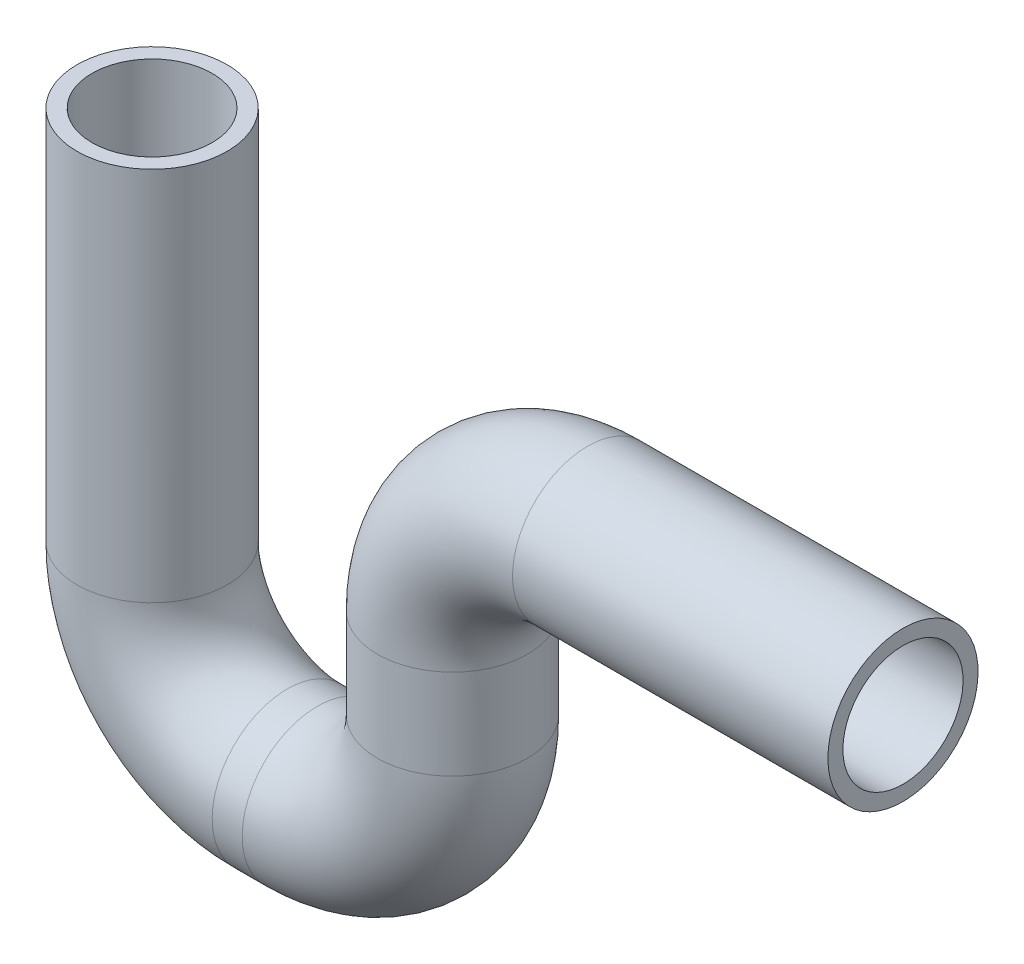
SolidWorks part; units mm, degrees
ref_plane "Alzado" through (0, 0, 0) normal (0, 0, 1) x (1, 0, 0)
ref_plane "Planta" through (0, 0, 0) normal (0, 1, 0) x (1, 0, 0)
ref_plane "Vista lateral" through (0, 0, 0) normal (1, 0, 0) x (0, 0, -1)
sketch "Croquis2" plane through (0, 0, 0) normal (0, 0, 1) x (1, 0, 0)
  line L0 (0, 0) -> (0, -125)
  line L1 (45, -170) -> (55, -170)
  line L2 (100, -125) -> (100, -95)
  line L3 (145, -50) -> (250, -50)
  arc A0 (100, -95) -> (145, -50) centre (145, -95) cw
  arc A1 (55, -170) -> (100, -125) centre (55, -125) ccw
  arc A2 (0, -125) -> (45, -170) centre (45, -125) ccw
  point P7 (100, -50)
  point P10 (100, -170)
  point P13 (0, -170)
  point P14 (0, 0)
  dimension "D5" = 45
  dimension "D1" = 120
  dimension "D2" = 170
  dimension "D3" = 100
  dimension "D4" = 150
sketch "Croquis3" plane through (0, 0, 0) normal (0, 1, 0) x (1, 0, 0)
  circle A0 centre (0, 0) radius 25
  circle A1 centre (0, 0) radius 20
  dimension "D1" = 50
  dimension "D2" = 40
sweep "Barrer1" add profiles "Croquis3" path "Croquis2"
